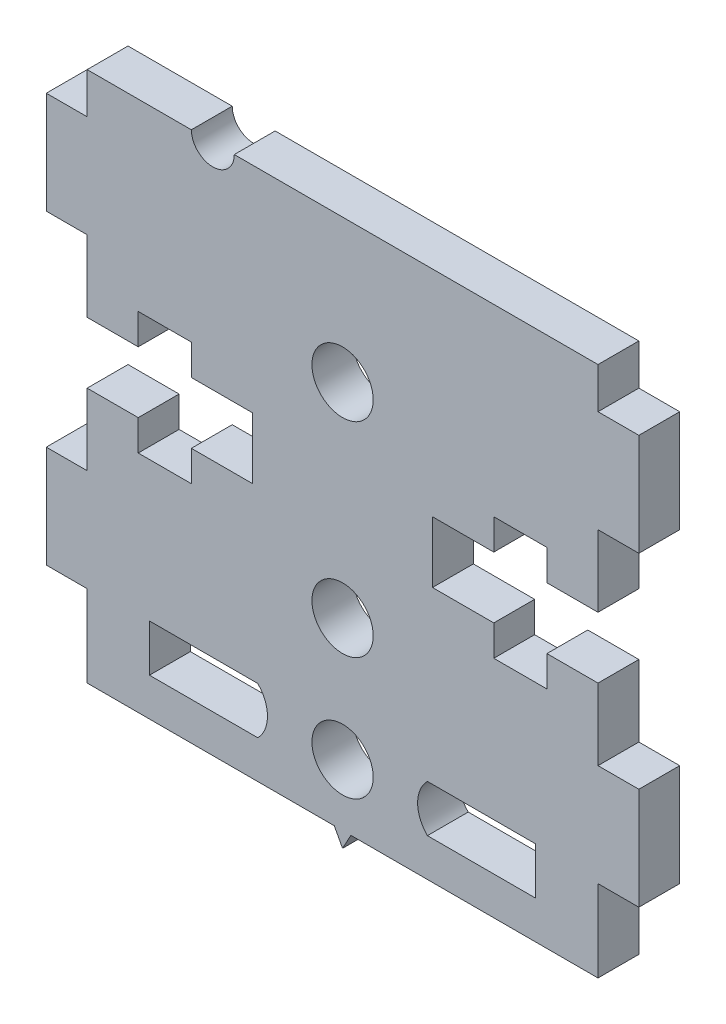
SolidWorks part; units mm, degrees
ref_plane "前视基准面" through (0, 0, 0) normal (0, 0, 1) x (1, 0, 0)
ref_plane "上视基准面" through (0, 0, 0) normal (0, 1, 0) x (1, 0, 0)
ref_plane "右视基准面" through (0, 0, 0) normal (1, 0, 0) x (0, 0, -1)
sketch "草图1" plane through (0, 0, 0) normal (0, 0, 1) x (1, 0, 0)
  line L1 (-8.6829, -11.201) -> (-10.6829, -11.201)
  line L2 (-10.6829, -11.201) -> (-10.6829, -6.201)
  line L6 (-8.6829, -11.201) -> (-8.6829, -15.201)
  line L8 (3.8171, -6.201) -> (16.3171, -6.201) construction
  line L26 (-10.6829, -6.201) -> (-8.6829, -6.201)
  line L33 (-8.6829, 3.799) -> (-10.6829, 3.799)
  line L34 (-10.6829, 3.799) -> (-10.6829, 8.799)
  line L35 (-10.6829, 8.799) -> (-8.6829, 8.799)
  line L36 (-8.6829, 8.799) -> (-8.6829, 10.799)
  line L37 (16.3171, 8.799) -> (16.3171, 10.799)
  line L38 (18.3171, 8.799) -> (16.3171, 8.799)
  line L39 (18.3171, 3.799) -> (18.3171, 8.799)
  line L40 (16.3171, 3.799) -> (18.3171, 3.799)
  line L42 (18.3171, -6.201) -> (16.3171, -6.201)
  line L47 (16.3171, -11.201) -> (16.3171, -15.201)
  line L48 (18.3171, -11.201) -> (18.3171, -6.201)
  line L49 (16.3171, -11.201) -> (18.3171, -11.201)
  line L55 (13.1171, -11.201) -> (8.1171, -11.201) construction
  line L57 (13.2671, -13.3428) -> (7.9671, -13.3428)
  line L58 (13.2671, -11.0428) -> (13.2671, -13.3428)
  line L63 (-5.4829, -11.201) -> (-0.4829, -11.201) construction
  line L64 (-5.4829, -11.201) -> (-5.4829, -11.0428)
  line L65 (-5.4829, -11.0428) -> (-5.6329, -11.0428)
  line L66 (13.2671, -11.0428) -> (7.9671, -11.0428)
  line L67 (-5.6329, -11.0428) -> (-0.3329, -11.0428)
  line L68 (-5.6329, -11.0428) -> (-5.6329, -13.3428)
  line L69 (-5.6329, -13.3428) -> (-0.3329, -13.3428)
  line L71 (13.1171, -11.0428) -> (13.2671, -11.0428)
  line L72 (13.1171, -11.201) -> (13.1171, -11.0428)
  line L74 (3.8171, -6.201) -> (3.8171, 3.799) construction
  line L76 (3.8171, -15.9558) -> (4.223, -15.201)
  line L77 (4.223, -15.201) -> (16.3171, -15.201)
  line L81 (3.8171, -15.9558) -> (3.4111, -15.201)
  line L82 (-8.6829, -15.201) -> (3.4111, -15.201)
  line L85 (3.8171, -6.201) -> (3.8171, -15.9558) construction
  line L86 (3.8171, -13.9021) -> (-8.6829, -13.9021) construction
  line L87 (3.8171, -13.9021) -> (16.3171, -13.9021) construction
  line L88 (3.8171, 3.799) -> (3.8171, 10.0204) construction
  line L89 (3.8171, 8.799) -> (16.3171, 8.799) construction
  line L90 (3.8171, -6.201) -> (-8.6829, -6.201) construction
  line L91 (-6.1829, -2.701) -> (-6.1829, -4.201)
  line L92 (-0.5829, 0.299) -> (-0.5829, -2.701)
  line L93 (-6.1829, 0.299) -> (-6.1829, 1.799)
  line L94 (-8.6829, 0.299) -> (-6.1829, 0.299)
  line L95 (-6.1829, -4.201) -> (-3.5829, -4.201)
  line L96 (-3.5829, -4.201) -> (-3.5829, -2.701)
  line L97 (-3.5829, -2.701) -> (-0.5829, -2.701)
  line L98 (-3.5829, 0.299) -> (-0.5829, 0.299)
  line L99 (-3.5829, 1.799) -> (-3.5829, 0.299)
  line L100 (-6.1829, 1.799) -> (-3.5829, 1.799)
  line L101 (-6.1829, -2.701) -> (-8.6829, -2.701)
  line L102 (-8.6829, -1.201) -> (-7.0556, -1.201) construction
  line L103 (-8.6829, 3.799) -> (-8.6829, 0.299)
  line L104 (-8.6829, -2.701) -> (-8.6829, -6.201)
  line L105 (-6.1829, 0.299) -> (-8.6829, 0.299)
  line L106 (-6.1829, -4.201) -> (-3.5829, -4.201)
  line L107 (-3.5829, -4.201) -> (-3.5829, -2.701)
  line L108 (-3.5829, -2.701) -> (-0.5829, -2.701)
  line L109 (-3.5829, 0.299) -> (-0.5829, 0.299)
  line L110 (-3.5829, 1.799) -> (-3.5829, 0.299)
  line L111 (-6.1829, 1.799) -> (-3.5829, 1.799)
  line L112 (-8.6829, -2.701) -> (-6.1829, -2.701)
  line L113 (-6.1829, -2.701) -> (-6.1829, -4.201)
  line L114 (-6.1829, 0.299) -> (-6.1829, 1.799)
  line L115 (16.3171, -1.201) -> (14.6897, -1.201) construction
  line L116 (13.8171, 0.299) -> (13.8171, 1.799)
  line L117 (13.8171, -2.701) -> (13.8171, -4.201)
  line L118 (16.3171, -2.701) -> (13.8171, -2.701)
  line L119 (13.8171, 1.799) -> (11.2171, 1.799)
  line L120 (11.2171, 1.799) -> (11.2171, 0.299)
  line L121 (11.2171, 0.299) -> (8.2171, 0.299)
  line L122 (11.2171, -2.701) -> (8.2171, -2.701)
  line L123 (11.2171, -4.201) -> (11.2171, -2.701)
  line L124 (13.8171, -4.201) -> (11.2171, -4.201)
  line L125 (13.8171, 0.299) -> (16.3171, 0.299)
  line L126 (13.8171, -2.701) -> (16.3171, -2.701)
  line L127 (13.8171, 1.799) -> (11.2171, 1.799)
  line L128 (11.2171, 1.799) -> (11.2171, 0.299)
  line L129 (11.2171, 0.299) -> (8.2171, 0.299)
  line L130 (11.2171, -2.701) -> (8.2171, -2.701)
  line L131 (11.2171, -4.201) -> (11.2171, -2.701)
  line L132 (13.8171, -4.201) -> (11.2171, -4.201)
  line L133 (16.3171, 0.299) -> (13.8171, 0.299)
  line L134 (13.8171, 0.299) -> (13.8171, 1.799)
  line L135 (8.2171, 0.299) -> (8.2171, -2.701)
  line L136 (13.8171, -2.701) -> (13.8171, -4.201)
  line L137 (16.3171, 3.799) -> (16.3171, 0.299)
  line L138 (16.3171, -2.701) -> (16.3171, -6.201)
  line L139 (-8.6829, 10.799) -> (-3.5829, 10.799)
  line L140 (-1.4829, 10.799) -> (16.3171, 10.799)
  circle A6 centre (3.8171, -6.201) radius 1.5
  circle A7 centre (3.8171, 3.799) radius 1.5
  arc A8 (-0.3329, -11.0428) -> (-0.3329, -13.3428) centre (-1.4829, -12.1928) cw
  arc A9 (7.9671, -11.0428) -> (7.9671, -13.3428) centre (9.1171, -12.1928) ccw
  circle A10 centre (3.8171, -12.1928) radius 1.5
  arc A11 (-3.5829, 10.799) -> (-1.4829, 10.799) centre (-2.5329, 10.799) ccw
extrude "凸台-拉伸1" add sketch "草图1" along normal blind 2
sketch "草图2" plane through (-8.6829, 0, 0) normal (-1, 0, 0) x (0, 0, 1)
  line L0 (1, 0.299) -> (1, -2.701)
  line L1 (2, 0.299) -> (0, 0.299) construction
  line L2 (2, -2.701) -> (0, -2.701) construction
  circle A0 centre (1, -1.201) radius 1.5
sketch "草图3" plane through (16.3171, 0, 0) normal (1, 0, 0) x (0, 0, -1)
  line L0 (-1, 0.299) -> (-1, -2.701)
  line L1 (-2, 0.299) -> (0, 0.299) construction
  line L2 (-2, -2.701) -> (0, -2.701) construction
  circle A0 centre (-1, -1.201) radius 1.5
